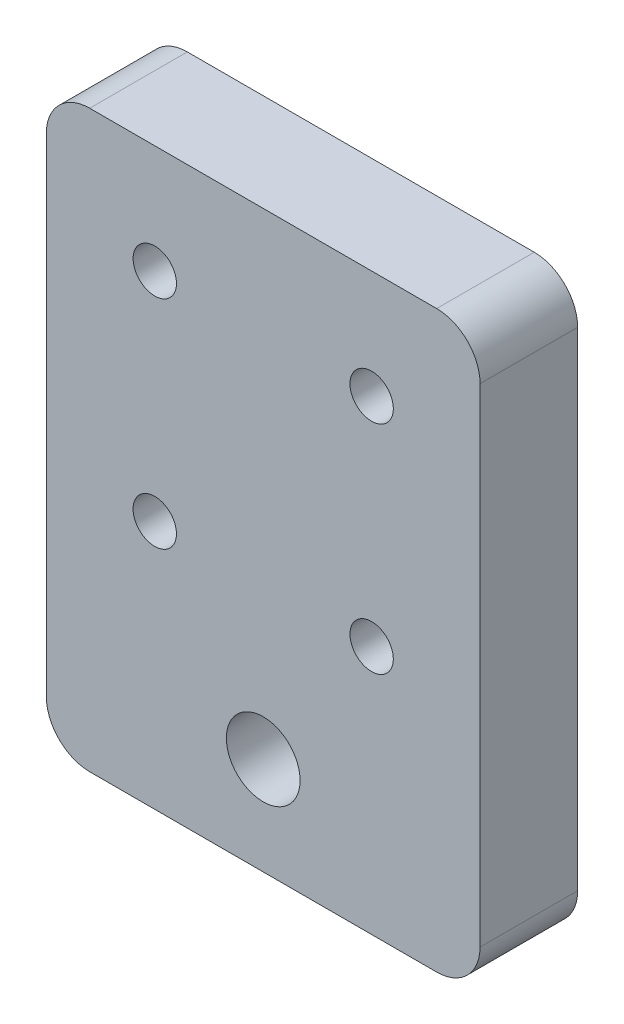
SolidWorks part; units mm, degrees
ref_plane "Front" through (0, 0, 0) normal (0, 0, 1) x (1, 0, 0)
ref_plane "Top" through (0, 0, 0) normal (0, 1, 0) x (1, 0, 0)
ref_plane "Right" through (0, 0, 0) normal (1, 0, 0) x (0, 0, -1)
sketch "Esquisse1" plane through (0, 0, 0) normal (0, 0, 1) x (1, 0, 0)
  line L1 (0, 0) -> (40, 0)
  line L2 (0, 0) -> (0, 53)
  line L3 (0, 53) -> (40, 53)
  line L4 (40, 0) -> (40, 53)
  dimension "D1" = 53
  dimension "D2" = 40
extrude "Boss.-Extru.1" add sketch "Esquisse1" along normal blind 9
sketch "Esquisse2" plane through (0, 0, 9) normal (0, 0, 1) x (1, 0, 0)
  line L0 (0, 33) -> (40, 33) construction
  line L3 (20, 53) -> (20, 0) construction
  line L4 (40, 53) -> (0, 53) construction
  line L5 (0, 0) -> (40, 0) construction
  line L6 (0, 53) -> (0, 0) construction
  line L7 (40, 0) -> (40, 53) construction
  circle A0 centre (10, 43) radius 2
  circle A1 centre (30, 43) radius 2
  circle A2 centre (30, 23) radius 2
  circle A3 centre (10, 23) radius 2
  circle A4 centre (20, 9) radius 3.4
  dimension "D1" = 20
  dimension "D3" = 4
  dimension "D4" = 6.8
  dimension "D2" = 20
  dimension "D5" = 20
  dimension "D6" = 24
extrude "Enlèv. mat.-Extru.1" cut sketch "Esquisse2" against normal through all
fillet "Congé1" radius 4 4 edges at (40, 53, 4.5) (40, 0, 4.5) (0, 0, 4.5) (0, 53, 4.5)
